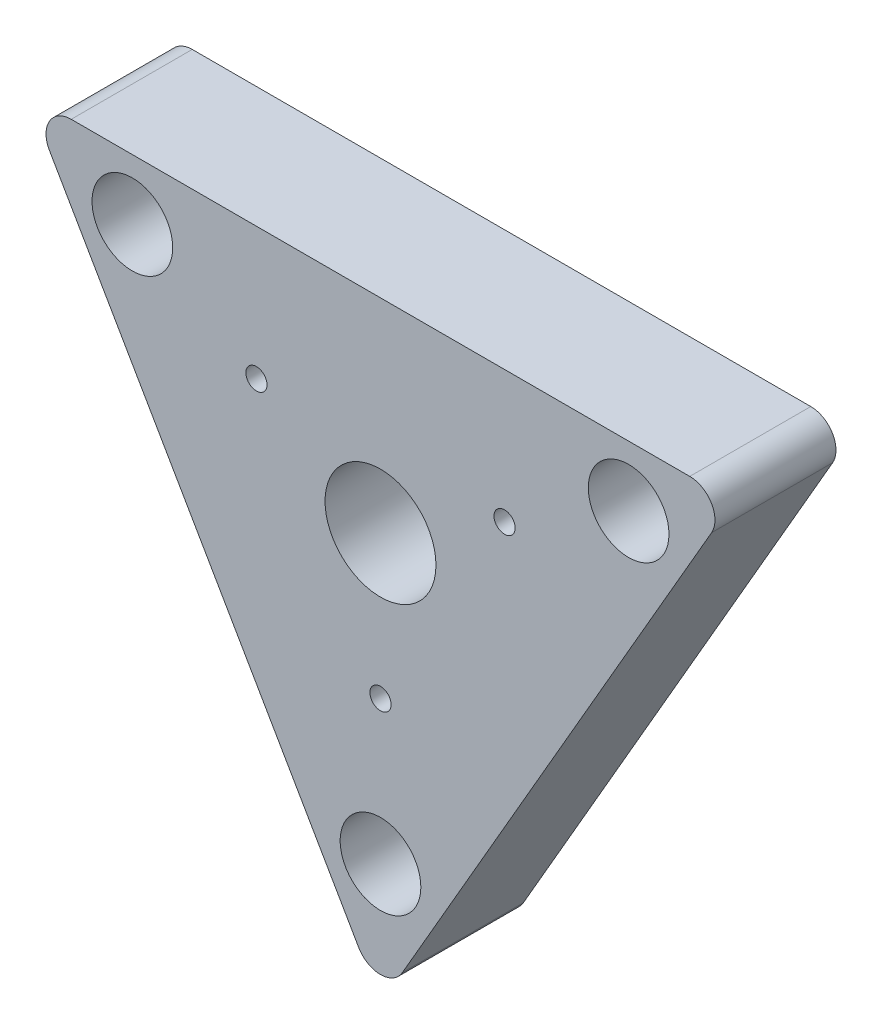
SolidWorks part; units mm, degrees
ref_plane "Ön Düzlem" through (0, 0, 0) normal (0, 0, 1) x (1, 0, 0)
ref_plane "Üst Düzlem" through (0, 0, 0) normal (0, 1, 0) x (1, 0, 0)
ref_plane "Sağ Düzlem" through (0, 0, 0) normal (1, 0, 0) x (0, 0, -1)
sketch "Çizim2" plane through (0, 0, 0) normal (0, 0, 1) x (1, 0, 0)
  line L0 (-52.9545, 36.1772) -> (69.725, 36.1772)
  line L1 (74.0552, 28.6772) -> (12.7154, -77.5664)
  line L2 (4.0552, -77.5664) -> (-57.2846, 28.6772)
  line L3 (-57.2846, 33.6772) -> (43.3853, -24.4446)
  line L4 (8.3853, 36.1772) -> (8.3853, -80.0664)
  line L5 (-26.6147, -24.4446) -> (74.0552, 33.6772)
  line L6 (74.0552, 33.6772) -> (57.6007, 24.1772)
  line L7 (8.3853, -80.0664) -> (8.3853, -61.0664)
  line L8 (-57.2846, 33.6772) -> (-40.8301, 24.1772)
  line L9 (43.3853, -24.4446) -> (8.3853, -4.2373)
  arc A0 (12.7154, -77.5664) -> (4.0552, -77.5664) centre (8.3853, -75.0664) cw
  arc A1 (69.725, 36.1772) -> (74.0552, 28.6772) centre (69.725, 31.1772) cw
  arc A2 (-52.9545, 36.1772) -> (-57.2846, 28.6772) centre (-52.9545, 31.1772) ccw
  circle A3 centre (57.6007, 24.1772) radius 8
  circle A4 centre (8.3853, -61.0664) radius 8
  circle A5 centre (-40.8301, 24.1772) radius 8
  circle A6 centre (8.3853, -4.2373) radius 11
  dimension "D2" = 5
  dimension "D4" = 16
  dimension "D6" = 22
  dimension "D1" = 19
  dimension "D3" = 19
  dimension "D5" = 19
extrude "Yükseklik-Ekstrüzyon1" add sketch "Çizim2" along normal blind 24 contours A5 L3 A2 L2 L5 | A5 L3 L4 L0 A2 | A3 L6 A1 L0 L4 L5 | A3 L5 L3 L1 A1 L6 | A4 L7 A0 L1 L3 L4 | A4 L4 L5 L2 A0 L7
sketch "Çizim3" plane through (0, 0, 24) normal (0, 0, 1) x (1, 0, 0)
  circle A0 centre (-40.8301, 24.1772) radius 4
  circle A1 centre (57.6007, 24.1772) radius 4
  circle A2 centre (8.3853, -61.0664) radius 4
  dimension "D1" = 8
sketch "Çizim4" plane through (0, 0, 24) normal (0, 0, 1) x (1, 0, 0)
  line L0 (-40.8301, 24.1772) -> (8.3853, -4.2373)
  line L1 (8.3853, -4.2373) -> (8.3853, -61.0664)
  line L2 (8.3853, -61.0664) -> (8.3853, -4.2373)
  line L3 (8.3853, -4.2373) -> (57.6007, 24.1772)
  circle A0 centre (-16.2224, 9.9699) radius 2.8241
  circle A1 centre (32.993, 9.9699) radius 2.8445
  circle A2 centre (8.3853, -32.6518) radius 4.1972
hole_wizard "M4 Helisarmal için Zıvana matkabı1" positions "3B Çizim1" profile "Çizim5" hole size "M4x0.7" standard "ANSI Metric" end condition up to next
sketch3d "3B Çizim1"
  point P0 (-16.2224, 9.9699, 24)
  point P3 (32.993, 9.9699, 24)
  point P6 (8.3853, -32.6518, 24)
sketch "Çizim5" plane through (-16.2224, 9.9699, 24) normal (1, 0, 0) x (0, -1, 0)
  line L0 (0, 0) -> (0, 24)
  line L1 (0, 24) -> (2.1, 24)
  line L2 (2.1, 24) -> (2.1, 0)
  line L5 (2.1, 0) -> (0, 0)
  line L11 (0, -6.35) -> (0, 107.95) construction
  dimension "Thru Hole Dia." = 4.2
  dimension "Thru Hole Depth" = 24
